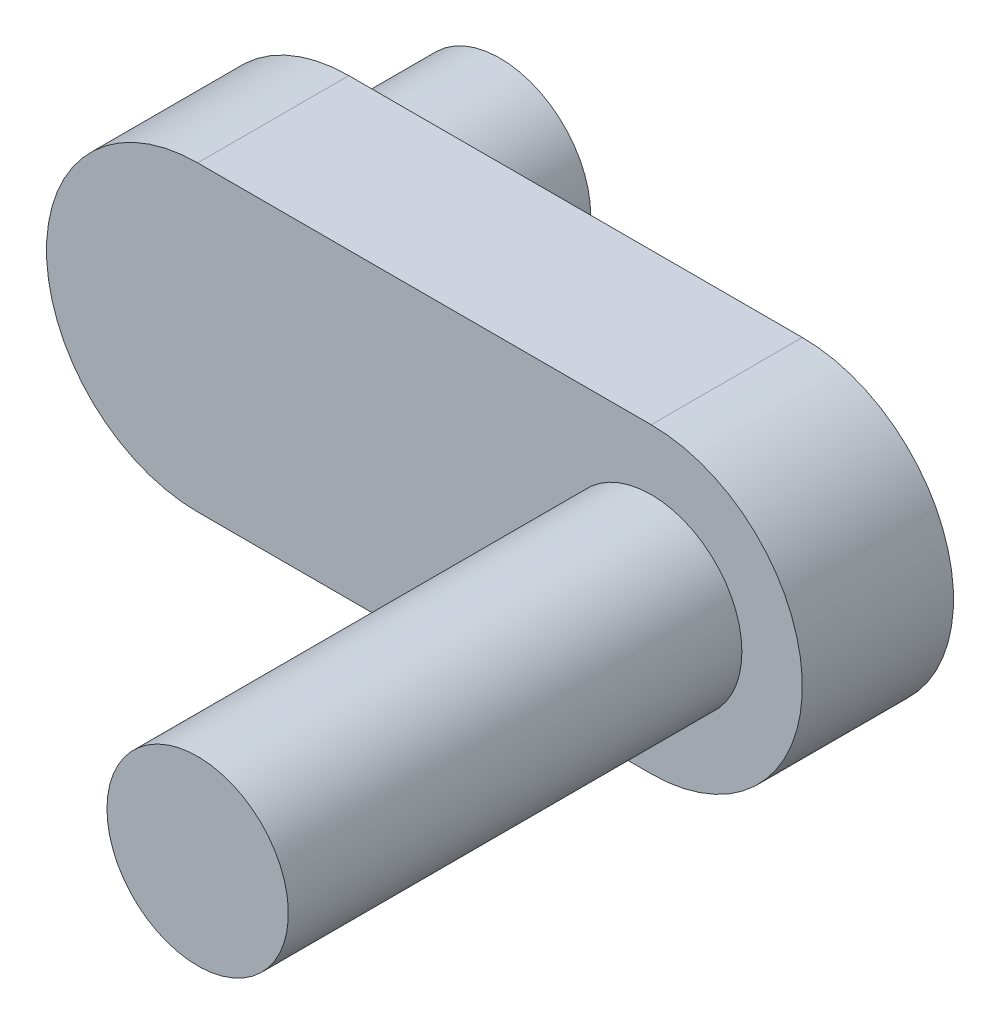
SolidWorks part; units mm, degrees
ref_plane "Front Plane" through (0, 0, 0) normal (0, 0, 1) x (1, 0, 0)
ref_plane "Top Plane" through (0, 0, 0) normal (0, 1, 0) x (1, 0, 0)
ref_plane "Right Plane" through (0, 0, 0) normal (1, 0, 0) x (0, 0, -1)
sketch "Sketch1" plane through (0, 0, 0) normal (0, 0, 1) x (1, 0, 0)
  line L0 (7.5, 0) -> (-7.5, 0) construction
  line L1 (7.5, -5) -> (-7.5, -5)
  line L2 (7.5, 5) -> (-7.5, 5)
  arc A0 (7.5, -5) -> (7.5, 5) centre (7.5, 0) ccw
  arc A1 (-7.5, 5) -> (-7.5, -5) centre (-7.5, 0) ccw
  circle A2 centre (-7.5, 0) radius 3
  circle A3 centre (7.5, 0) radius 3
  point P2 (0, 0)
  dimension "D2" = 5
  dimension "D3" = 6
  dimension "D4" = 6
  dimension "D1" = 15
extrude "Boss-Extrude1" add sketch "Sketch1" along normal blind 5
sketch "Sketch2" plane through (0, 0, 5) normal (0, 0, 1) x (1, 0, 0)
  circle A0 centre (-7.5, 0) radius 3
extrude "Boss-Extrude2" add sketch "Sketch2" against normal blind 10
sketch "Sketch3" plane through (0, 0, 0) normal (0, 0, -1) x (-1, 0, 0)
  circle A0 centre (-7.5, 0) radius 3
extrude "Boss-Extrude3" add sketch "Sketch3" against normal blind 20
